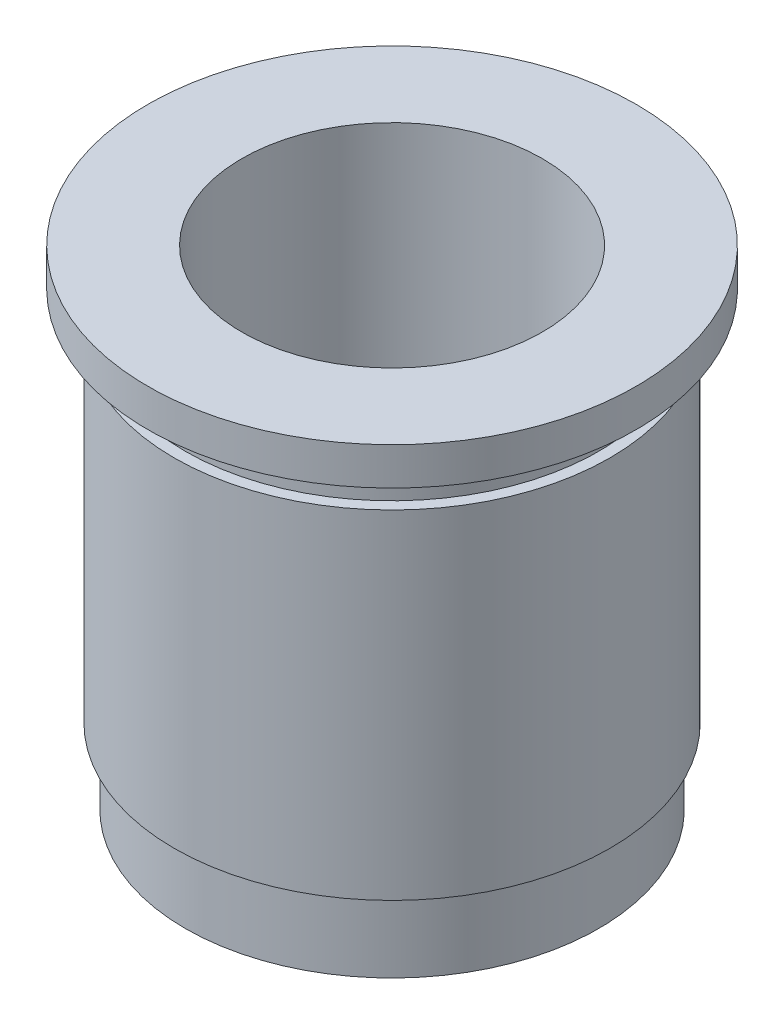
SolidWorks part; units mm, degrees
ref_plane "正面" through (0, 0, 0) normal (0, 0, 1) x (1, 0, 0)
ref_plane "平面" through (0, 0, 0) normal (0, 1, 0) x (1, 0, 0)
ref_plane "右側面" through (0, 0, 0) normal (1, 0, 0) x (0, 0, -1)
sketch "ｽｹｯﾁ1" plane through (0, 0, 0) normal (0, 0, 1) x (1, 0, 0)
  line L0 (0, 0) -> (0, 6.5) construction
  line L2 (2, 6.5) -> (3.25, 6.5)
  line L3 (2.75, 5.5) -> (2.9, 5.5)
  line L4 (2.75, 6) -> (3.25, 6)
  line L5 (3.25, 6.5) -> (3.25, 6)
  line L7 (2, 6.5) -> (2, 0)
  line L8 (2, 0) -> (2.75, 0)
  line L9 (2.75, 6) -> (2.75, 5.5)
  line L10 (2.75, 1) -> (2.9, 1)
  line L11 (2.9, 5.5) -> (2.9, 1)
  line L18 (2.75, 1) -> (2.75, 0)
  dimension "D1" = 6.5
  dimension "D2" = 3.25
  dimension "D3" = 0.5
  dimension "D4" = 4
  dimension "D5" = 5.5
  dimension "D6" = 5.8
  dimension "D7" = 1
  dimension "D8" = 0.5
revolve "回転1" add sketch "ｽｹｯﾁ1" angle 360 about L0
